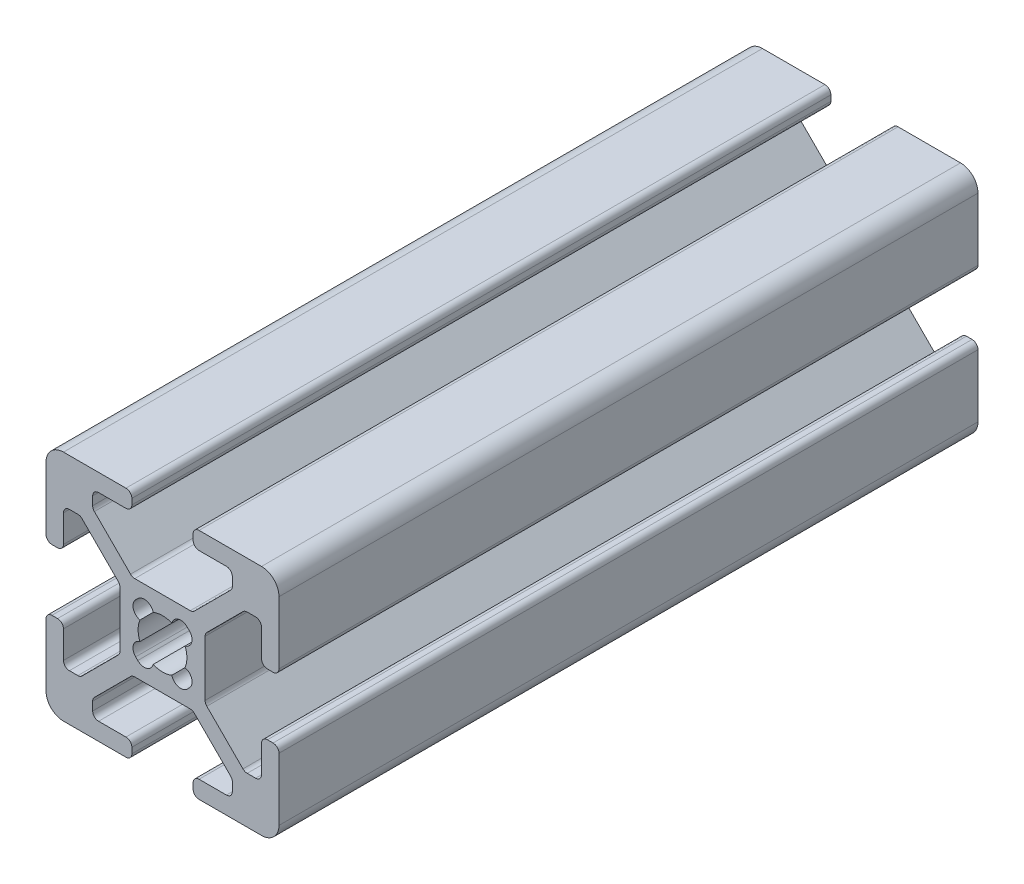
SolidWorks part; units mm, degrees
material "1060 Alloy"
ref_plane "Front Plane" through (0, 0, 0) normal (0, 0, 1) x (1, 0, 0)
ref_plane "Top Plane" through (0, 0, 0) normal (0, 1, 0) x (1, 0, 0)
ref_plane "Right Plane" through (0, 0, 0) normal (1, 0, 0) x (0, 0, -1)
sketch "Sketch2" plane through (0, 0, 0) normal (0, 0, 1) x (1, 0, 0)
  line L0 (-10, -3.138) -> (-10, -8.5)
  line L1 (-8.5, -10) -> (-3.138, -10)
  line L2 (-2.63, -9.492) -> (-2.63, -9.008)
  line L3 (-3.138, -8.5) -> (-5.487, -8.5)
  line L4 (-5.995, -7.992) -> (-5.995, -7.2662)
  line L5 (-5.8462, -6.907) -> (-2.743, -3.8038)
  line L6 (-2.3838, -3.655) -> (2.3841, -3.655)
  line L7 (2.7433, -3.8038) -> (5.8462, -6.9067)
  line L8 (5.995, -7.2659) -> (5.995, -7.992)
  line L9 (5.487, -8.5) -> (3.138, -8.5)
  line L10 (2.63, -9.008) -> (2.63, -9.492)
  line L11 (3.138, -10) -> (8.5, -10)
  line L12 (10, -8.5) -> (10, -3.138)
  line L13 (9.492, -2.63) -> (9.008, -2.63)
  line L14 (8.5, -3.138) -> (8.5, -5.487)
  line L15 (7.992, -5.995) -> (7.2662, -5.995)
  line L16 (6.907, -5.8462) -> (3.8038, -2.743)
  line L17 (3.655, -2.3838) -> (3.655, 2.3841)
  line L18 (3.8038, 2.7433) -> (6.9067, 5.8462)
  line L19 (7.2659, 5.995) -> (7.992, 5.995)
  line L20 (8.5, 5.487) -> (8.5, 3.138)
  line L21 (9.008, 2.63) -> (9.492, 2.63)
  line L22 (10, 3.138) -> (10, 8.5)
  line L23 (8.5, 10) -> (3.138, 10)
  line L24 (2.63, 9.492) -> (2.63, 9.008)
  line L25 (3.138, 8.5) -> (5.487, 8.5)
  line L26 (5.995, 7.992) -> (5.995, 7.2662)
  line L27 (5.8462, 6.907) -> (2.743, 3.8038)
  line L28 (2.3838, 3.655) -> (-2.3841, 3.655)
  line L29 (-2.7433, 3.8038) -> (-5.8462, 6.9067)
  line L30 (-5.995, 7.2659) -> (-5.995, 7.992)
  line L31 (-5.487, 8.5) -> (-3.138, 8.5)
  line L32 (-2.63, 9.008) -> (-2.63, 9.492)
  line L33 (-3.138, 10) -> (-8.5, 10)
  line L34 (-10, 8.5) -> (-10, 3.138)
  line L35 (-9.492, 2.63) -> (-9.008, 2.63)
  line L36 (-8.5, 3.138) -> (-8.5, 5.487)
  line L37 (-7.992, 5.995) -> (-7.2662, 5.995)
  line L38 (-6.907, 5.8462) -> (-3.8038, 2.743)
  line L39 (-3.655, 2.3838) -> (-3.655, -2.3841)
  line L40 (-3.8038, -2.7433) -> (-6.9067, -5.8462)
  line L41 (-7.2659, -5.995) -> (-7.992, -5.995)
  line L42 (-8.5, -5.487) -> (-8.5, -3.138)
  line L43 (-9.008, -2.63) -> (-9.492, -2.63)
  line L44 (-2.1245, 2.3045) -> (-2.3045, 2.1245)
  line L45 (2.3045, 2.1245) -> (2.1245, 2.3045)
  line L46 (2.1245, -2.3045) -> (2.3045, -2.1245)
  line L47 (-2.3045, -2.1245) -> (-2.1245, -2.3045)
  arc A0 (-10, -8.5) -> (-8.5, -10) centre (-8.5, -8.5) ccw
  arc A1 (-3.138, -10) -> (-2.63, -9.492) centre (-3.138, -9.492) ccw
  arc A2 (-2.63, -9.008) -> (-3.138, -8.5) centre (-3.138, -9.008) ccw
  arc A3 (-5.995, -7.992) -> (-5.487, -8.5) centre (-5.487, -7.992) ccw
  arc A4 (-5.8462, -6.907) -> (-5.995, -7.2662) centre (-5.487, -7.2662) ccw
  arc A5 (-2.3838, -3.655) -> (-2.743, -3.8038) centre (-2.3838, -4.163) ccw
  arc A6 (2.7433, -3.8038) -> (2.3841, -3.655) centre (2.3841, -4.163) ccw
  arc A7 (5.995, -7.2659) -> (5.8462, -6.9067) centre (5.487, -7.2659) ccw
  arc A8 (5.487, -8.5) -> (5.995, -7.992) centre (5.487, -7.992) ccw
  arc A9 (3.138, -8.5) -> (2.63, -9.008) centre (3.138, -9.008) ccw
  arc A10 (2.63, -9.492) -> (3.138, -10) centre (3.138, -9.492) ccw
  arc A11 (8.5, -10) -> (10, -8.5) centre (8.5, -8.5) ccw
  arc A12 (10, -3.138) -> (9.492, -2.63) centre (9.492, -3.138) ccw
  arc A13 (9.008, -2.63) -> (8.5, -3.138) centre (9.008, -3.138) ccw
  arc A14 (7.992, -5.995) -> (8.5, -5.487) centre (7.992, -5.487) ccw
  arc A15 (6.907, -5.8462) -> (7.2662, -5.995) centre (7.2662, -5.487) ccw
  arc A16 (3.655, -2.3838) -> (3.8038, -2.743) centre (4.163, -2.3838) ccw
  arc A17 (3.8038, 2.7433) -> (3.655, 2.3841) centre (4.163, 2.3841) ccw
  arc A18 (7.2659, 5.995) -> (6.9067, 5.8462) centre (7.2659, 5.487) ccw
  arc A19 (8.5, 5.487) -> (7.992, 5.995) centre (7.992, 5.487) ccw
  arc A20 (8.5, 3.138) -> (9.008, 2.63) centre (9.008, 3.138) ccw
  arc A21 (9.492, 2.63) -> (10, 3.138) centre (9.492, 3.138) ccw
  arc A22 (10, 8.5) -> (8.5, 10) centre (8.5, 8.5) ccw
  arc A23 (3.138, 10) -> (2.63, 9.492) centre (3.138, 9.492) ccw
  arc A24 (2.63, 9.008) -> (3.138, 8.5) centre (3.138, 9.008) ccw
  arc A25 (5.995, 7.992) -> (5.487, 8.5) centre (5.487, 7.992) ccw
  arc A26 (5.8462, 6.907) -> (5.995, 7.2662) centre (5.487, 7.2662) ccw
  arc A27 (2.3838, 3.655) -> (2.743, 3.8038) centre (2.3838, 4.163) ccw
  arc A28 (-2.7433, 3.8038) -> (-2.3841, 3.655) centre (-2.3841, 4.163) ccw
  arc A29 (-5.995, 7.2659) -> (-5.8462, 6.9067) centre (-5.487, 7.2659) ccw
  arc A30 (-5.487, 8.5) -> (-5.995, 7.992) centre (-5.487, 7.992) ccw
  arc A31 (-3.138, 8.5) -> (-2.63, 9.008) centre (-3.138, 9.008) ccw
  arc A32 (-2.63, 9.492) -> (-3.138, 10) centre (-3.138, 9.492) ccw
  arc A33 (-8.5, 10) -> (-10, 8.5) centre (-8.5, 8.5) ccw
  arc A34 (-10, 3.138) -> (-9.492, 2.63) centre (-9.492, 3.138) ccw
  arc A35 (-9.008, 2.63) -> (-8.5, 3.138) centre (-9.008, 3.138) ccw
  arc A36 (-7.992, 5.995) -> (-8.5, 5.487) centre (-7.992, 5.487) ccw
  arc A37 (-6.907, 5.8462) -> (-7.2662, 5.995) centre (-7.2662, 5.487) ccw
  arc A38 (-3.655, 2.3838) -> (-3.8038, 2.743) centre (-4.163, 2.3838) ccw
  arc A39 (-3.8038, -2.7433) -> (-3.655, -2.3841) centre (-4.163, -2.3841) ccw
  arc A40 (-7.2659, -5.995) -> (-6.9067, -5.8462) centre (-7.2659, -5.487) ccw
  arc A41 (-8.5, -5.487) -> (-7.992, -5.995) centre (-7.992, -5.487) ccw
  arc A42 (-8.5, -3.138) -> (-9.008, -2.63) centre (-9.008, -3.138) ccw
  arc A43 (-9.492, -2.63) -> (-10, -3.138) centre (-9.492, -3.138) ccw
  arc A44 (-1.9358, 0.8037) -> (-1.9358, -0.8037) centre (0, 0) ccw
  arc A45 (-2.3045, 2.1245) -> (-1.9358, 0.8037) centre (-1.748, 1.568) ccw
  arc A46 (-0.8037, 1.9358) -> (-2.1245, 2.3045) centre (-1.568, 1.748) ccw
  arc A47 (0.8037, 1.9358) -> (-0.8037, 1.9358) centre (0, 0) ccw
  arc A48 (2.1245, 2.3045) -> (0.8037, 1.9358) centre (1.568, 1.748) ccw
  arc A49 (1.9358, 0.8037) -> (2.3045, 2.1245) centre (1.748, 1.568) ccw
  arc A50 (1.9358, -0.8037) -> (1.9358, 0.8037) centre (0, 0) ccw
  arc A51 (2.3045, -2.1245) -> (1.9358, -0.8037) centre (1.748, -1.568) ccw
  arc A52 (0.8037, -1.9358) -> (2.1245, -2.3045) centre (1.568, -1.748) ccw
  arc A53 (-0.8037, -1.9358) -> (0.8037, -1.9358) centre (0, 0) ccw
  arc A54 (-2.1245, -2.3045) -> (-0.8037, -1.9358) centre (-1.568, -1.748) ccw
  arc A55 (-1.9358, -0.8037) -> (-2.3045, -2.1245) centre (-1.748, -1.568) ccw
extrude "Boss-Extrude1" add sketch "Sketch2" against normal blind 60
